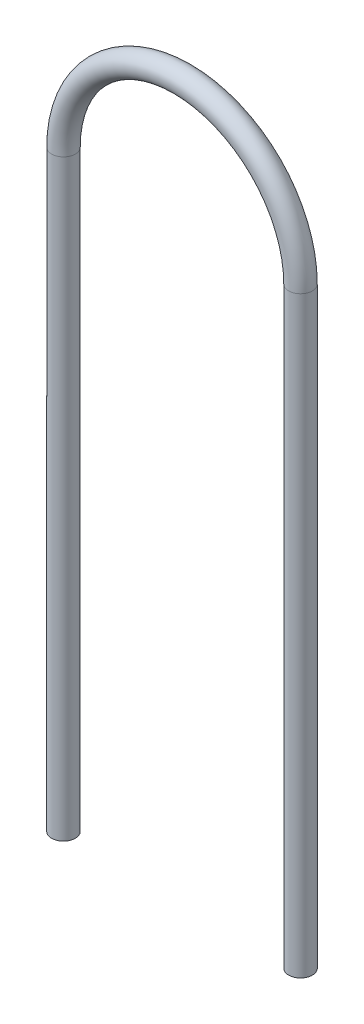
SolidWorks part; units mm, degrees
ref_plane "Front Plane" through (0, 0, 0) normal (0, 0, 1) x (1, 0, 0)
ref_plane "Top Plane" through (0, 0, 0) normal (0, 1, 0) x (1, 0, 0)
ref_plane "Right Plane" through (0, 0, 0) normal (1, 0, 0) x (0, 0, -1)
sketch "Sketch1" plane through (0, 0, 0) normal (0, 0, 1) x (1, 0, 0)
  line L0 (0, 0) -> (0, 500)
  line L1 (200, 500) -> (200, 0)
  arc A0 (0, 500) -> (200, 500) centre (100, 500) cw
  point P5 (0, 0)
  dimension "D1" = 500
  dimension "D2" = 200
sketch "Sketch2" plane through (0, 0, 0) normal (0, 1, 0) x (1, 0, 0)
  circle A0 centre (0, 0) radius 10
  dimension "D1" = 20
sweep "Sweep1" add profiles "Sketch2" path "Sketch1"
